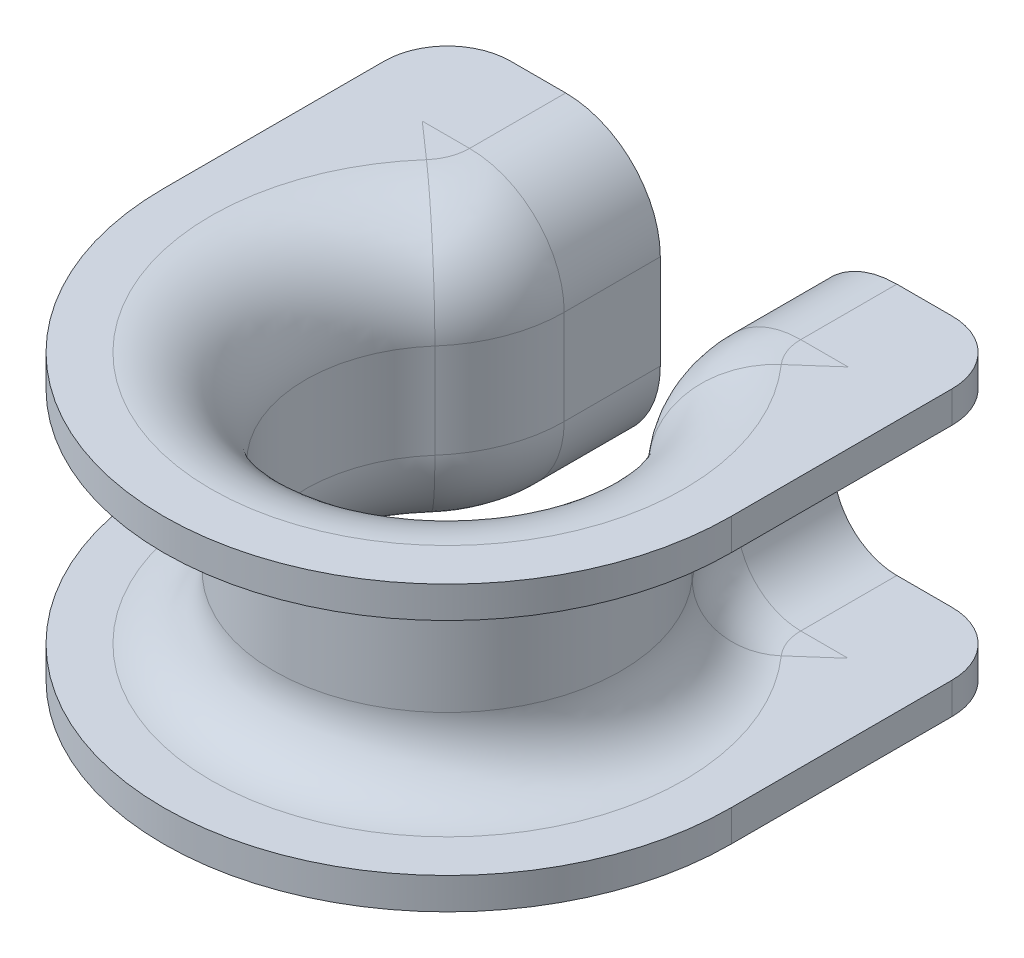
SolidWorks part; units mm, degrees
ref_plane "Front Plane" through (0, 0, 0) normal (0, 0, 1) x (1, 0, 0)
ref_plane "Top Plane" through (0, 0, 0) normal (0, 1, 0) x (1, 0, 0)
ref_plane "Right Plane" through (0, 0, 0) normal (1, 0, 0) x (0, 0, -1)
sketch "Sketch1" plane through (0, 0, 0) normal (0, 1, 0) x (1, 0, 0)
  line L0 (4.5, 18) -> (4.5, 11.9059)
  line L1 (0, 0) -> (0, 24.4997) construction
  line L2 (-4.5, 18) -> (-4.5, 11.9059)
  arc A0 (-6.75, 5.9529) -> (6.75, 5.9529) centre (0, 0) ccw
  arc A1 (-4.5, 11.9059) -> (-6.75, 5.9529) centre (-13.5, 11.9059) cw
  arc A2 (4.5, 11.9059) -> (6.75, 5.9529) centre (13.5, 11.9059) ccw
  point P4 (0, 0)
  dimension "D1" = 18
  dimension "D4" = 9
  dimension "D2" = 9
  dimension "D3" = 18
sketch "Sketch2" plane through (0, 0, 0) normal (1, 0, 0) x (0, 0, -1)
  line L0 (-9, -3) -> (-9, 3)
  line L2 (-18, 9) -> (-18, 7)
  line L8 (5.9529, 0) -> (-9, 0) construction
  line L9 (-18, 9) -> (-15, 9)
  line L10 (-15, -9) -> (-18, -9)
  line L11 (-18, -9) -> (-18, -7)
  line L12 (-15, 7) -> (-18, 7)
  line L13 (-18, -7) -> (-15, -7)
  line L14 (-11, -3) -> (-11, 3)
  line L17 (-15, -7) -> (-16, -7) construction
  line L18 (-16, 7) -> (-15, 7) construction
  line L19 (-16, 7) -> (-16, 7) construction
  line L20 (-16, -7) -> (-16, -7) construction
  arc A0 (-15, 9) -> (-9, 3) centre (-15, 3) cw
  arc A1 (-9, -3) -> (-15, -9) centre (-15, -3) cw
  arc A2 (-15, 7) -> (-11, 3) centre (-15, 3) cw
  arc A3 (-11, -3) -> (-15, -7) centre (-15, -3) cw
  point P11 (-9, 0)
  dimension "D1" = 6
  dimension "D3" = 18
  dimension "D2" = 2
  dimension "D4" = 3
  dimension "D5" = 2
sweep "Sweep1" add profiles "Sketch2" path "Sketch1"
sketch "Sketch3" plane through (0, 0, -18) normal (0, 0, -1) x (-1, 0, 0)
  line L0 (18, -7) -> (-18, -7) construction
  line L1 (-13.5, -9) -> (-18, -9)
  line L2 (-13.5, -9) -> (-13.5, -7)
  line L3 (-13.5, -7) -> (-18, -7)
  line L4 (-18, -9) -> (-18, -7)
  line L6 (-13.5, 7) -> (-18, 7)
  line L7 (-13.5, 7) -> (-13.5, 9)
  line L8 (-13.5, 9) -> (-18, 9)
  line L9 (-18, 7) -> (-18, 9)
extrude "Boss-Extrude1" add sketch "Sketch3" against normal up to surface (18 mm away)
mirror "Mirror2" about plane through (0, 0, 0) normal (1, 0, 0) of "Boss-Extrude1"
fillet "Fillet1" radius 4 4 edges at (18, -8, -18) (18, 8, -18) (-18, -8, -18) (-18, 8, -18)
